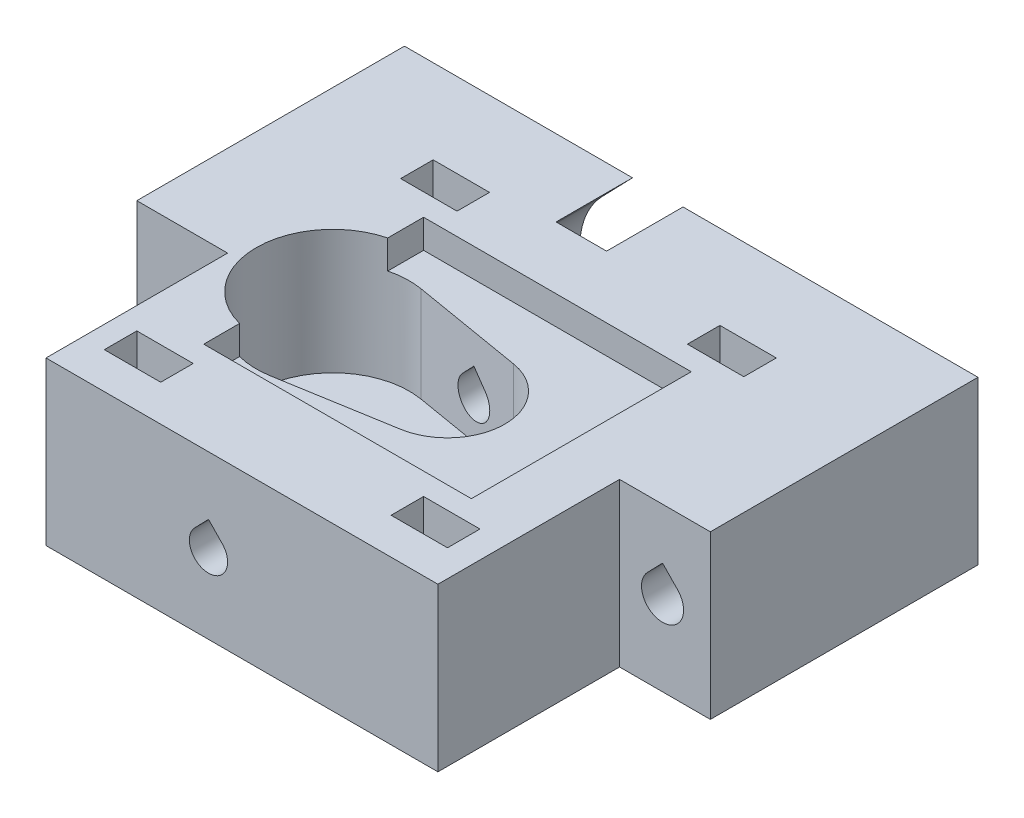
SolidWorks part; units mm, degrees
ref_plane "Front Plane" through (0, 0, 0) normal (0, 0, 1) x (1, 0, 0)
ref_plane "Top Plane" through (0, 0, 0) normal (0, 1, 0) x (1, 0, 0)
ref_plane "Right Plane" through (0, 0, 0) normal (1, 0, 0) x (0, 0, -1)
ref_plane "Plane1" through (-9.6515, 0, 0) normal (-1, 0, 0) x (0, -1, 0)
sketch "Sketch1" plane through (-9.6515, 0, 0) normal (-1, 0, 0) x (0, -1, 0)
  line L0 (0, -26) -> (17, -26)
  line L1 (17, -26) -> (17, 21)
  line L2 (17, 21) -> (0, 21)
  line L3 (0, 21) -> (0, -26)
extrude "Boss-Extrude1" add sketch "Sketch1" against normal blind 6.5811
sketch "Sketch2" plane through (0, 0, -26) normal (0, 0, -1) x (-1, 0, 0)
  line L0 (3.0704, 0) -> (3.0704, -17)
  line L1 (3.0704, -17) -> (9.6515, -17)
  line L2 (9.6515, -17) -> (9.6515, -8.8596)
  line L3 (7.3645, -3.3367) -> (4.1423, 0)
  line L4 (4.1423, 0) -> (3.0704, 0)
  arc A0 (9.6515, -8.8596) -> (7.3645, -3.3367) centre (1.5, -9) ccw
extrude "Cut-Extrude1" cut sketch "Sketch2" against normal blind 8
sketch "Sketch3" plane through (0, 0, -18) normal (0, 0, -1) x (-1, 0, 0)
  line L0 (9.6515, -9.1404) -> (9.6515, -17)
  line L1 (9.6515, -17) -> (3.0704, -17)
  arc A0 (3.0704, -17) -> (9.6515, -9.1404) centre (1.5, -9) ccw
extrude "Boss-Extrude2" add sketch "Sketch3" along normal blind 8
sketch "Sketch4" plane through (-3.0704, 0, 0) normal (1, 0, 0) x (0, 0, -1)
  line L0 (18, -17) -> (-21, -17)
  line L1 (-21, -17) -> (-21, 0)
  line L2 (-21, 0) -> (18, 0)
  line L3 (18, 0) -> (18, -17)
extrude "Boss-Extrude3" add sketch "Sketch4" along normal blind 35.0704
sketch "Sketch5" plane through (-9.6515, 0, 0) normal (-1, 0, 0) x (0, 0, 1)
  line L0 (21, -17) -> (-26, -17)
  line L1 (-26, -17) -> (-26, 0)
  line L2 (-26, 0) -> (21, 0)
  line L3 (21, 0) -> (21, -17)
extrude "Boss-Extrude4" add sketch "Sketch5" along normal blind 18.3485
sketch "Sketch6" plane through (0, 0, -18) normal (0, 0, -1) x (-1, 0, 0)
  line L0 (-32, -17) -> (-32, 0)
  line L1 (-32, 0) -> (-1.1423, 0)
  line L2 (-1.1423, 0) -> (-4.3645, -3.3367)
  line L3 (-0.0704, -17) -> (-32, -17)
  arc A0 (-4.3645, -3.3367) -> (-0.0704, -17) centre (1.5, -9) ccw
extrude "Boss-Extrude5" add sketch "Sketch6" along normal blind 8
sketch "Sketch7" plane through (0, 0, 0) normal (0, 1, 0) x (-1, 0, 0)
  line L0 (11.5, -11.5) -> (11.5, -7.746)
  line L1 (11.5, 7.746) -> (11.5, 11.5)
  line L2 (11.5, 11.5) -> (-16.5, 11.5)
  line L3 (-16.5, 11.5) -> (-16.5, -11.5)
  line L4 (-16.5, -11.5) -> (11.5, -11.5)
  arc A0 (11.5, -7.746) -> (11.5, 7.746) centre (9.5, 0) ccw
extrude "Cut-Extrude2" cut sketch "Sketch7" against normal blind 3
sketch "Sketch8" plane through (0, -3, 0) normal (0, 1, 0) x (-1, 0, 0)
  line L0 (-3.5, -5.9161) -> (8.1667, -7.8881)
  line L1 (8.1667, 7.8881) -> (-3.5, 5.9161)
  arc A0 (-3.5, 5.9161) -> (-3.5, -5.9161) centre (-2.5, 0) cw
  arc A1 (8.1667, -7.8881) -> (8.1667, 7.8881) centre (9.5, 0) ccw
extrude "Cut-Extrude3" cut sketch "Sketch8" against normal blind 10
sketch "Sketch9" plane through (0, -17, 0) normal (0, -1, 0) x (1, 0, 0)
  line L0 (32, 21) -> (22.5, 21)
  line L1 (22.5, 21) -> (22.5, 2)
  line L2 (22.5, 2) -> (32, 2)
  line L3 (32, 2) -> (32, 21)
extrude "Cut-Extrude4" cut sketch "Sketch9" against normal through all
sketch "Sketch10" plane through (0, -17, 0) normal (0, -1, 0) x (1, 0, 0)
  line L0 (-18.5, 2) -> (-18.5, 21)
  line L1 (-18.5, 21) -> (-28, 21)
  line L2 (-28, 21) -> (-28, 2)
  line L3 (-28, 2) -> (-18.5, 2)
extrude "Cut-Extrude5" cut sketch "Sketch10" against normal through all
sketch "Sketch11" plane through (0, -17, 0) normal (0, -1, 0) x (1, 0, 0)
  line L0 (-16.2, 13.8) -> (-10.3, 13.8)
  line L1 (-10.3, 13.8) -> (-10.3, 17.2)
  line L2 (-10.3, 17.2) -> (-16.2, 17.2)
  line L3 (-16.2, 17.2) -> (-16.2, 13.8)
extrude "Cut-Extrude6" cut sketch "Sketch11" against normal through all
sketch "Sketch12" plane through (0, -17, 0) normal (0, -1, 0) x (1, 0, 0)
  line L0 (19.7, 17.2) -> (13.8, 17.2)
  line L1 (13.8, 17.2) -> (13.8, 13.8)
  line L2 (13.8, 13.8) -> (19.7, 13.8)
  line L3 (19.7, 13.8) -> (19.7, 17.2)
extrude "Cut-Extrude7" cut sketch "Sketch12" against normal through all
sketch "Sketch13" plane through (0, -17, 0) normal (0, -1, 0) x (1, 0, 0)
  line L0 (19.7, -13.8) -> (13.8, -13.8)
  line L1 (13.8, -13.8) -> (13.8, -17.2)
  line L2 (13.8, -17.2) -> (19.7, -17.2)
  line L3 (19.7, -17.2) -> (19.7, -13.8)
extrude "Cut-Extrude8" cut sketch "Sketch13" against normal through all
sketch "Sketch14" plane through (0, 0, 21) normal (0, 0, 1) x (1, 0, 0)
  line L0 (-0.0613, -7.6107) -> (-1.5, -6.1209)
  line L1 (-1.5, -6.1209) -> (-2.9387, -7.6107)
  arc A0 (-2.9387, -7.6107) -> (-0.0613, -7.6107) centre (-1.5, -9) ccw
extrude "Cut-Extrude9" cut sketch "Sketch14" against normal up to next
sketch "Sketch15" plane through (0, 0, 2) normal (0, 0, 1) x (1, 0, 0)
  line L0 (-21.4175, -6.9718) -> (-23, -5.333)
  line L1 (-23, -5.333) -> (-24.5825, -6.9718)
  arc A0 (-24.5825, -6.9718) -> (-21.4175, -6.9718) centre (-23, -8.5) ccw
extrude "Cut-Extrude10" cut sketch "Sketch15" against normal through all
sketch "Sketch16" plane through (0, 0, 2) normal (0, 0, 1) x (1, 0, 0)
  line L0 (28.5825, -6.9718) -> (27, -5.333)
  line L1 (27, -5.333) -> (25.4175, -6.9718)
  arc A0 (25.4175, -6.9718) -> (28.5825, -6.9718) centre (27, -8.5) ccw
extrude "Cut-Extrude11" cut sketch "Sketch16" against normal through all
sketch "Sketch17" plane through (0, -17, 0) normal (0, -1, 0) x (1, 0, 0)
  line L0 (-16.2, -17.2) -> (-10.3, -17.2)
  line L1 (-10.3, -17.2) -> (-10.3, -13.8)
  line L2 (-10.3, -13.8) -> (-16.2, -13.8)
  line L3 (-16.2, -13.8) -> (-16.2, -17.2)
extrude "Cut-Extrude12" cut sketch "Sketch17" against normal through all
sketch "Sketch18" plane through (0, 0, -18) normal (0, 0, -1) x (-1, 0, 0)
  line L0 (1.5, -6.1209) -> (0.0613, -7.6107)
  line L1 (2.9387, -7.6107) -> (1.5, -6.1209)
  arc A0 (0.0613, -7.6107) -> (2.9387, -7.6107) centre (1.5, -9) ccw
extrude "Cut-Extrude13" cut sketch "Sketch18" against normal up to next
sketch "Sketch19" plane through (0, 0, 0) normal (0, 0, 1) x (1, 0, 0)
  line L0 (8.5, -3) -> (2.5, -3)
  line L1 (2.5, -3) -> (2.5, -17)
  line L2 (2.5, -17) -> (8.5, -17)
  line L3 (8.5, -17) -> (8.5, -3)
  line L4 (2.5, -3) -> (2.5, -17) construction
revolve "Cut-Revolve1" cut sketch "Sketch19" angle 360 about L4
hole_wizard "Hole1" positions "Sketch21" profile "Sketch20" legacy
sketch "Sketch21" plane through (0, -17, 0) normal (0, -1, 0) x (1, 0, 0)
  point P0 (-9.5, 0)
sketch "Sketch20" plane through (-9.5, -17, 0) normal (1, 0, 0) x (0, 0, -1)
  line L0 (0, 0) -> (0, 17)
  line L1 (0, 17) -> (2.1, 17)
  line L2 (2.1, 17) -> (2.1, 0)
  line L3 (2.1, 0) -> (0, 0)
  line L4 (0, 110) -> (0, -10) construction
  dimension "Diameter" = 4.2
  dimension "Depth" = 17
